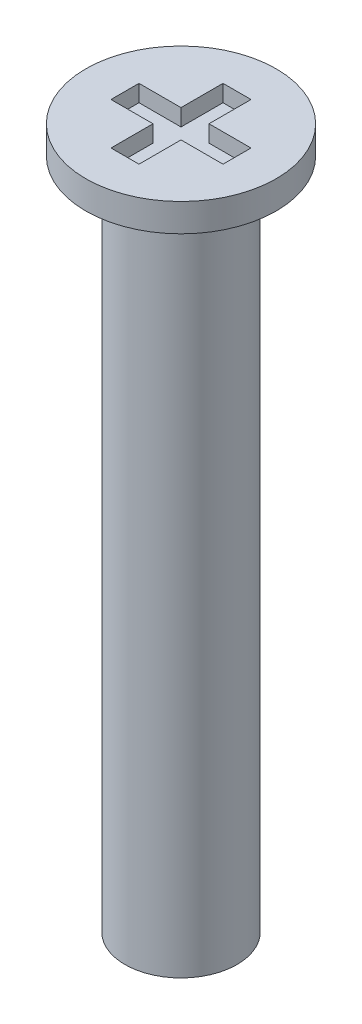
SolidWorks part; units mm, degrees
material "S45C"
ref_plane "正面" through (0, 0, 0) normal (0, 0, 1) x (1, 0, 0)
ref_plane "平面" through (0, 0, 0) normal (0, 1, 0) x (1, 0, 0)
ref_plane "右側面" through (0, 0, 0) normal (1, 0, 0) x (0, 0, -1)
sketch "ｽｹｯﾁ1" plane through (0, 0, 0) normal (0, 0, 1) x (1, 0, 0)
  line L0 (0, 0) -> (1.7, 0)
  line L1 (1.7, 0) -> (1.7, -0.5)
  line L2 (1.7, -0.5) -> (1, -0.5)
  line L3 (1, -0.5) -> (1, -12.5)
  line L4 (1, -12.5) -> (0, -12.5)
  line L5 (0, -12.5) -> (0, 0)
  dimension "D1" = 1.7
  dimension "D2" = 0.5
  dimension "D3" = 1
  dimension "D4" = 12
revolve "回転1" add sketch "ｽｹｯﾁ1" angle 360 about L5
sketch "ｽｹｯﾁ2" plane through (0, 0, 0) normal (0, 1, 0) x (1, 0, 0)
  line L1 (-0.25, 0) -> (0.25, 0)
  line L2 (-0.25, 0) -> (-0.25, 1)
  line L3 (-0.25, 1) -> (0.25, 1)
  line L4 (0.25, 0) -> (0.25, 1)
  line L5 (-0.25, 0) -> (0.25, 1) construction
  line L6 (-0.25, 1) -> (0.25, 0) construction
  point P4 (0, 0.5)
  dimension "D1" = 0
  dimension "D2" = 0.5
  dimension "D3" = 1
  dimension "D4" = 0
extrude "ｶｯﾄ - 押し出し1" cut sketch "ｽｹｯﾁ2" against normal blind 0.3
pattern_circular "円形ﾊﾟﾀｰﾝ1" count 4 over 360 about axis through (0, 0, 0) along (0, 1, 0) of "ｶｯﾄ - 押し出し1"
